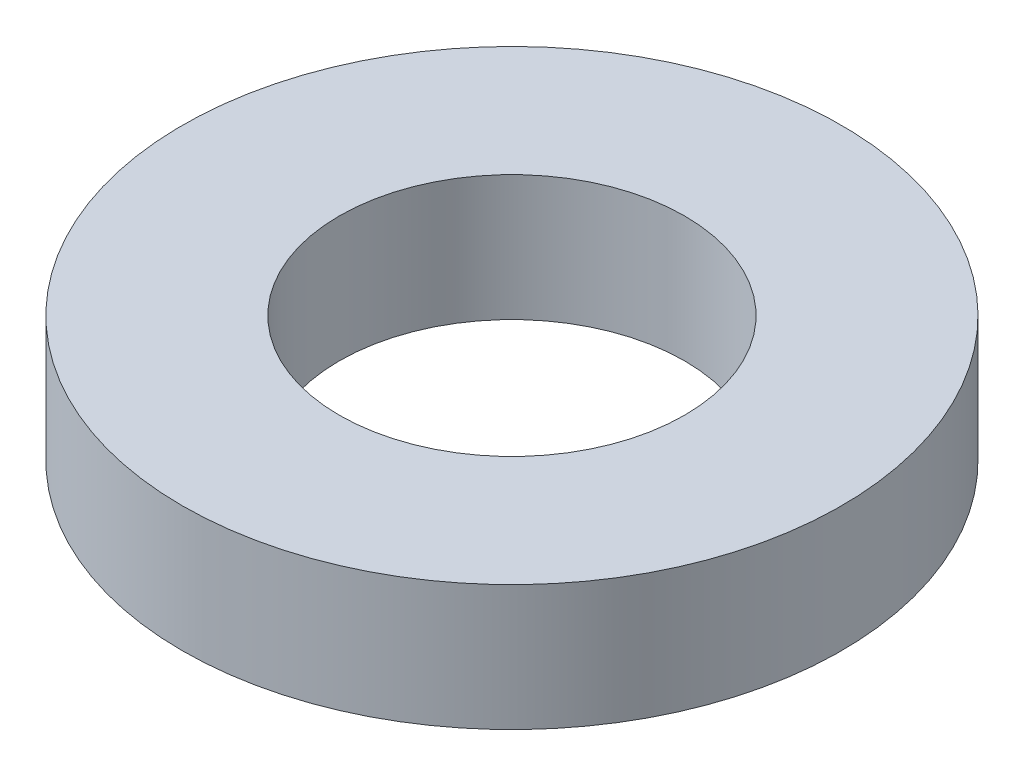
SolidWorks part; units mm, degrees
ref_plane "Front Plane" through (0, 0, 0) normal (0, 0, 1) x (1, 0, 0)
ref_plane "Top Plane" through (0, 0, 0) normal (0, 1, 0) x (1, 0, 0)
ref_plane "Right Plane" through (0, 0, 0) normal (1, 0, 0) x (0, 0, -1)
sketch "Sketch1" plane through (0, 0, 0) normal (0, 1, 0) x (1, 0, 0)
  circle A0 centre (0, 0) radius 1.65
  circle A1 centre (0, 0) radius 3.15
  dimension "D1" = 3.3
  dimension "D2" = 6.3
extrude "Boss-Extrude1" add sketch "Sketch1" along normal blind 1.2
